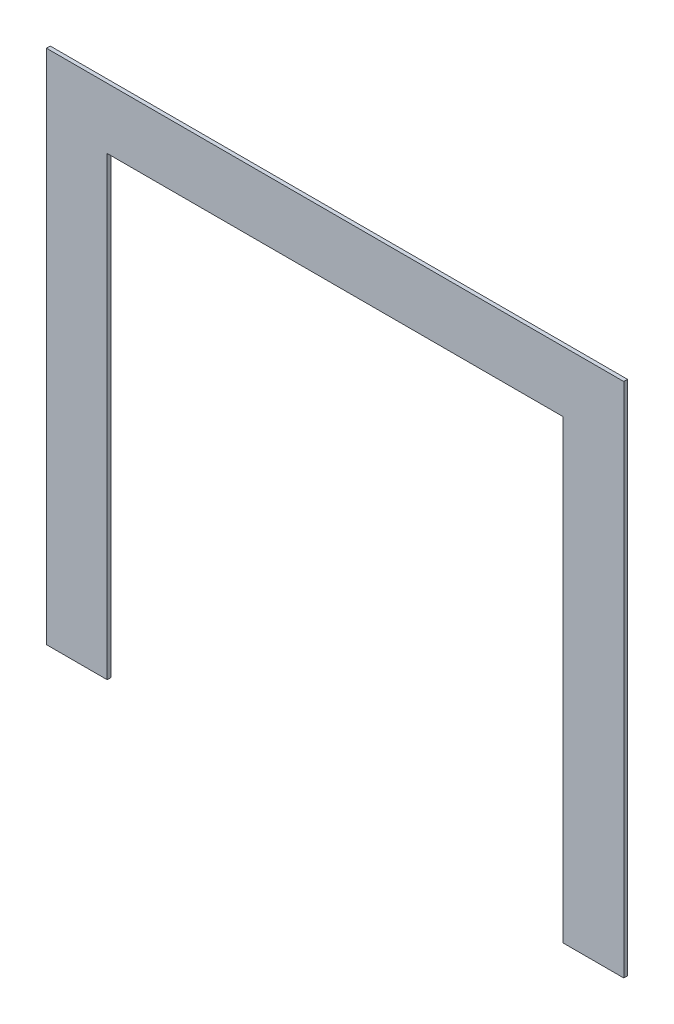
SolidWorks part; units mm, degrees
ref_plane "Front Plane" through (0, 0, 0) normal (0, 0, 1) x (1, 0, 0)
ref_plane "Top Plane" through (0, 0, 0) normal (0, 1, 0) x (1, 0, 0)
ref_plane "Right Plane" through (0, 0, 0) normal (1, 0, 0) x (0, 0, -1)
sketch "Sketch1" plane through (0, 0, 0) normal (0, 0, 1) x (1, 0, 0)
  line L1 (0, 0) -> (482.6, 0)
  line L2 (0, 0) -> (0, 431.8)
  line L3 (0, 431.8) -> (482.6, 431.8)
  line L4 (482.6, 0) -> (482.6, 431.8)
  dimension "D1" = 482.6
  dimension "D2" = 431.8
extrude "Boss-Extrude1" add sketch "Sketch1" along normal blind 3.175
sketch "Sketch2" plane through (0, 0, 3.175) normal (0, 0, 1) x (1, 0, 0)
  line L0 (0, 0) -> (482.6, 0) construction
  line L1 (50.8, 0) -> (431.8, 0)
  line L2 (50.8, 0) -> (50.8, 381)
  line L3 (50.8, 381) -> (431.8, 381)
  line L4 (431.8, 0) -> (431.8, 381)
  line L5 (0, 431.8) -> (0, 0) construction
  line L6 (482.6, 0) -> (482.6, 431.8) construction
  line L7 (482.6, 431.8) -> (0, 431.8) construction
  dimension "D1" = 50.8
  dimension "D2" = 50.8
  dimension "D3" = 50.8
extrude "Cut-Extrude1" cut sketch "Sketch2" against normal up to surface (3.175 mm away) up to face at (241.3, 215.9, 0)
